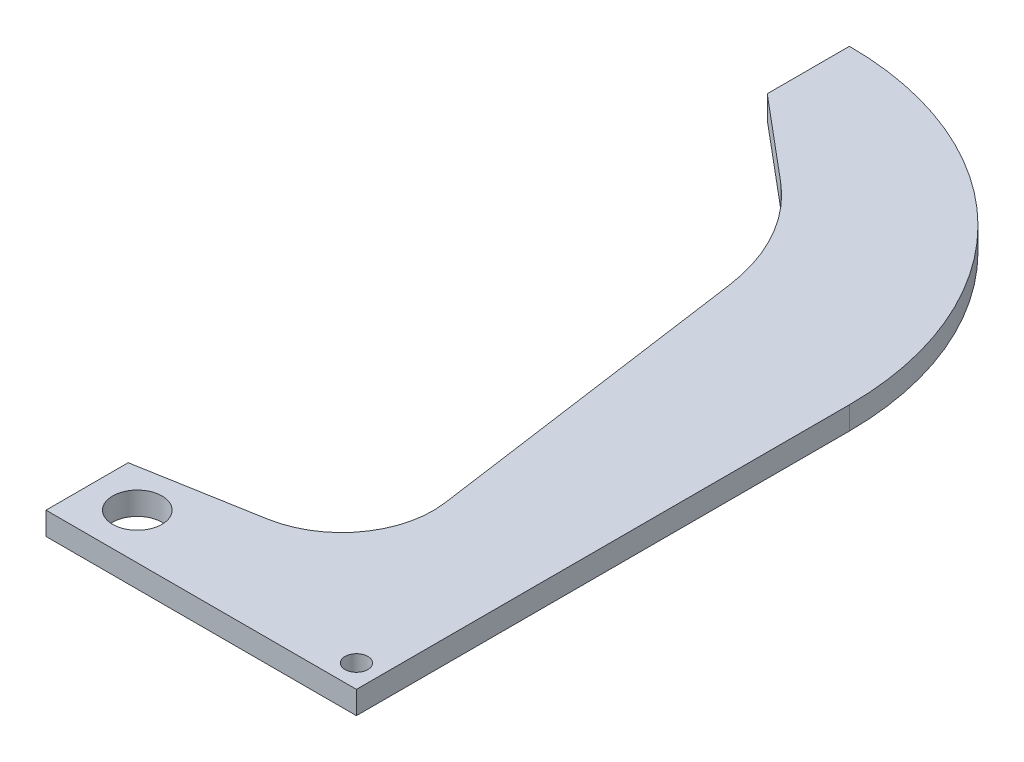
SolidWorks part; units mm, degrees
ref_plane "Front Plane" through (0, 0, 0) normal (0, 0, 1) x (1, 0, 0)
ref_plane "Top Plane" through (0, 0, 0) normal (0, 1, 0) x (1, 0, 0)
ref_plane "Right Plane" through (0, 0, 0) normal (1, 0, 0) x (0, 0, -1)
sketch "Sketch1" plane through (0, 0, 0) normal (0, 1, 0) x (1, 0, 0)
  line L1 (0, 0) -> (43.18, 0)
  line L2 (0, 0) -> (0, 111.76)
  line L4 (43.18, 0) -> (43.18, 68.58)
  circle A0 centre (6.35, 6.35) radius 3.429
  circle A1 centre (40.005, 3.175) radius 1.5875
  arc A2 (43.18, 68.58) -> (0, 111.76) centre (0, 68.58) ccw
  dimension "D3" = 6.858
  dimension "D6" = 3.175
  dimension "D1" = 43.18
  dimension "D4" = 6.35
  dimension "D5" = 6.35
  dimension "D7" = 3.175
  dimension "D8" = 3.175
  dimension "D2" = 111.76
extrude "Boss-Extrude1" add sketch "Sketch1" along normal blind 3.175
sketch "Sketch2" plane through (0, 3.175, 0) normal (0, 1, 0) x (1, 0, 0)
  line L1 (0, 111.76) -> (0, 0) construction
  line L2 (16.4996, 14.3393) -> (0, 11.43)
  line L3 (0, 11.43) -> (0, 100.33)
  line L4 (26.871, 28.6113) -> (20.4054, 74.6866)
  line L5 (11.5786, 90.6144) -> (0, 100.33)
  arc A0 (20.4054, 74.6866) -> (11.5786, 90.6144) centre (-4.7482, 71.1568) ccw
  arc A1 (26.871, 28.6113) -> (16.4996, 14.3393) centre (14.2943, 26.8464) cw
  point P4 (19.05, 22.4285)
  point P8 (30.4954, 29.0365)
  point P11 (19.05, 84.3452)
  point P14 (28.575, 16.4685)
  dimension "D7" = 25.4
  dimension "D8" = 12.7
  dimension "D1" = 88.9
  dimension "D2" = 11.43
  dimension "D3" = 50
  dimension "D4" = 80
  dimension "D5" = 19.05
  dimension "D6" = 28.575
extrude "Cut-Extrude1" cut sketch "Sketch2" against normal through all
equation "\"tightTol\" = 0.005in"
equation "\"normTol\"= 0.01in"
equation "\"looseTol\"= 0.02in"
equation "\"D3@Sketch1\"=\"looseTol\"+0.25"
